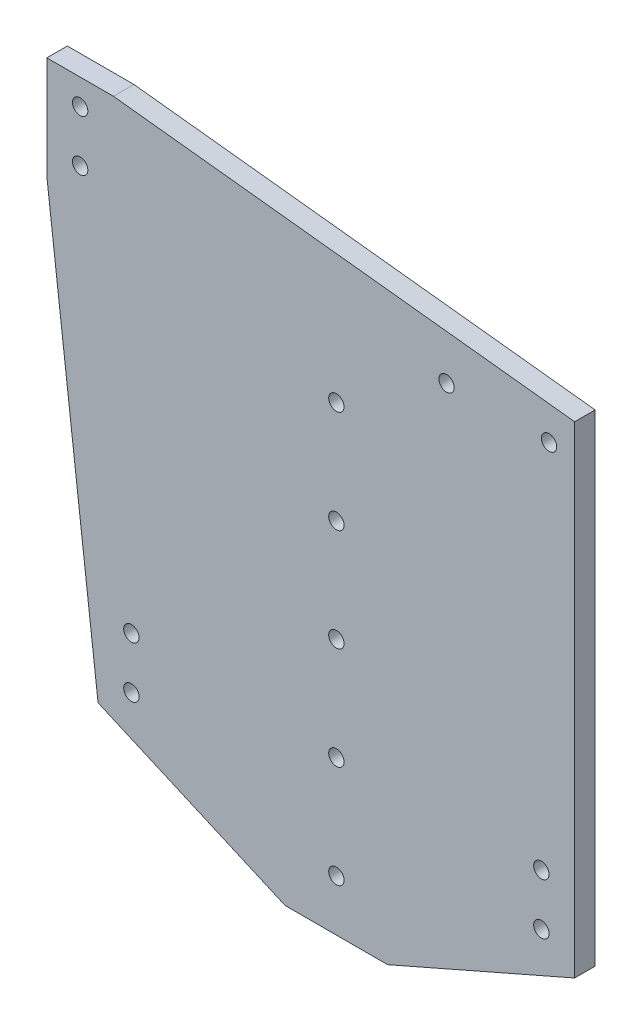
SolidWorks part; units mm, degrees
ref_plane "前视基准面" through (0, 0, 0) normal (0, 0, 1) x (1, 0, 0)
ref_plane "上视基准面" through (0, 0, 0) normal (0, 1, 0) x (1, 0, 0)
ref_plane "右视基准面" through (0, 0, 0) normal (1, 0, 0) x (0, 0, -1)
other "Configuration Table"
sketch "草图1" plane through (0, 0, 0) normal (0, 0, 1) x (1, 0, 0)
  line L0 (0, 0) -> (0, 94)
  line L4 (-46.5, -16) -> (-46.5, 99.1667) construction
  line L5 (-93.9615, 10) -> (-46.5, 10) construction
  line L6 (-86.5, 10) -> (-86.5, 0) construction
  line L7 (-93, 0) -> (-56.5, -16)
  line L8 (-56.5, -16) -> (-36.5, -16)
  line L9 (-36.5, -16) -> (0, 0)
  line L10 (-93, 0) -> (0, 0) construction
  line L11 (-96.5, 99) -> (-96.5, 89) construction
  line L12 (-46.5, 14) -> (-46.5, 34) construction
  line L13 (0, 88) -> (-5, 88) construction
  line L14 (-5, 88) -> (-25, 88) construction
  line L16 (-103, 104) -> (-90, 104)
  line L17 (-90, 104) -> (0, 94)
  line L18 (-96.5, 99) -> (-96.5, 104) construction
  line L19 (-103, 104) -> (-103, 84)
  line L20 (-103, 84) -> (-93, 0)
  circle A0 centre (-86.5, 15) radius 1.5
  circle A1 centre (-86.5, 5) radius 1.5
  circle A2 centre (-6.5, 5) radius 1.5
  circle A3 centre (-6.5, 15) radius 1.5
  circle A4 centre (-96.5, 99) radius 1.5
  circle A5 centre (-96.5, 89) radius 1.5
  circle A11 centre (-46.5, 14) radius 1.5
  circle A12 centre (-46.5, 34) radius 1.5
  circle A13 centre (-46.5, 54) radius 1.5
  circle A14 centre (-46.5, 74) radius 1.5
  circle A15 centre (-46.5, -6) radius 1.5
  circle A16 centre (-25, 88) radius 1.5
  circle A17 centre (-5, 88) radius 1.5
  point P17 (-86.5, 5)
  point P24 (-46.5, -16)
  dimension "D1" = 3
  dimension "D3" = 6.5
  dimension "D4" = 80
  dimension "D10" = 3
  dimension "D12" = 13
  dimension "D13" = 3
  dimension "D17" = 2
  dimension "D18" = 20
  dimension "D21" = 3
  dimension "D24" = 5
  dimension "D2" = 20
  dimension "D5" = 94
  dimension "D6" = 10
  dimension "D7" = 16
  dimension "D9" = 10
  dimension "D11" = 50
  dimension "D15" = 4
  dimension "D14" = 4
  dimension "D16" = 20
  dimension "D19" = 20
  dimension "D20" = 5
  dimension "D22" = 93
  dimension "D23" = 104
  dimension "D25" = 6
  dimension "D26" = 20
  dimension "D8" = 2
extrude "凸台-拉伸1" add sketch "草图1" along normal blind 4
